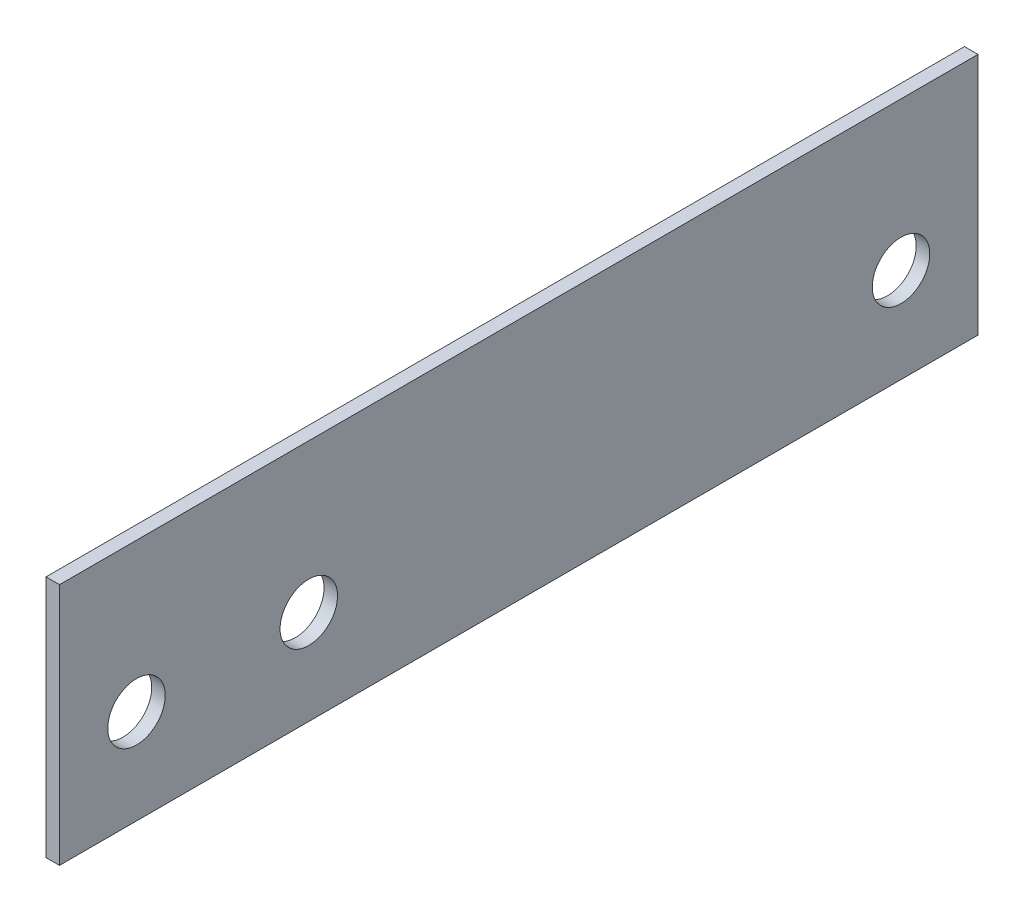
SolidWorks part; units mm, degrees
material "6061 Alloy"
ref_plane "Front" through (0, 0, 0) normal (0, 0, 1) x (1, 0, 0)
ref_plane "Top" through (0, 0, 0) normal (0, 1, 0) x (1, 0, 0)
ref_plane "Right" through (0, 0, 0) normal (1, 0, 0) x (0, 0, -1)
sketch "Sketch1" plane through (0, 0, 0) normal (1, 0, 0) x (0, 0, -1)
  line L1 (-53.975, -14.2875) -> (53.975, -14.2875)
  line L2 (-53.975, -14.2875) -> (-53.975, 14.2875)
  line L3 (-53.975, 14.2875) -> (53.975, 14.2875)
  line L4 (53.975, -14.2875) -> (53.975, 14.2875)
  line L5 (-53.975, -14.2875) -> (53.975, 14.2875) construction
  line L6 (-53.975, 14.2875) -> (53.975, -14.2875) construction
  point P0 (0, 0)
  dimension "D1" = 107.95
  dimension "D2" = 28.575
extrude "Boss-Extrude1" add sketch "Sketch1" along normal blind 1.5875 contours L2 L3 L4 L1
hole_wizard "1/4 Clearance Hole1" positions "Sketch2" profile "Sketch3" hole size "1/4" standard "ANSI Inch" end condition through all
sketch "Sketch2" plane through (-6.35, -14.6685, 57.15) normal (-1, 0, 0) x (0, 1, 0)
  point P0 (11.4935, 32.4749)
  point P3 (11.4935, 12.2244)
  point P6 (11.4935, 102.0756)
sketch "Sketch3" plane through (-6.35, -3.175, 24.6751) normal (0, 1, 0) x (0, 0, 1)
  line L0 (0, 0) -> (0, 7.9375)
  line L1 (0, 7.9375) -> (3.3782, 7.9375)
  line L2 (3.3782, 7.9375) -> (3.3782, 0)
  line L3 (3.3782, 0) -> (0, 0)
  line L4 (0, -6.35) -> (0, 107.95) construction
  dimension "Thru Hole Dia." = 6.7564
  dimension "Thru Hole Depth" = 7.9375
